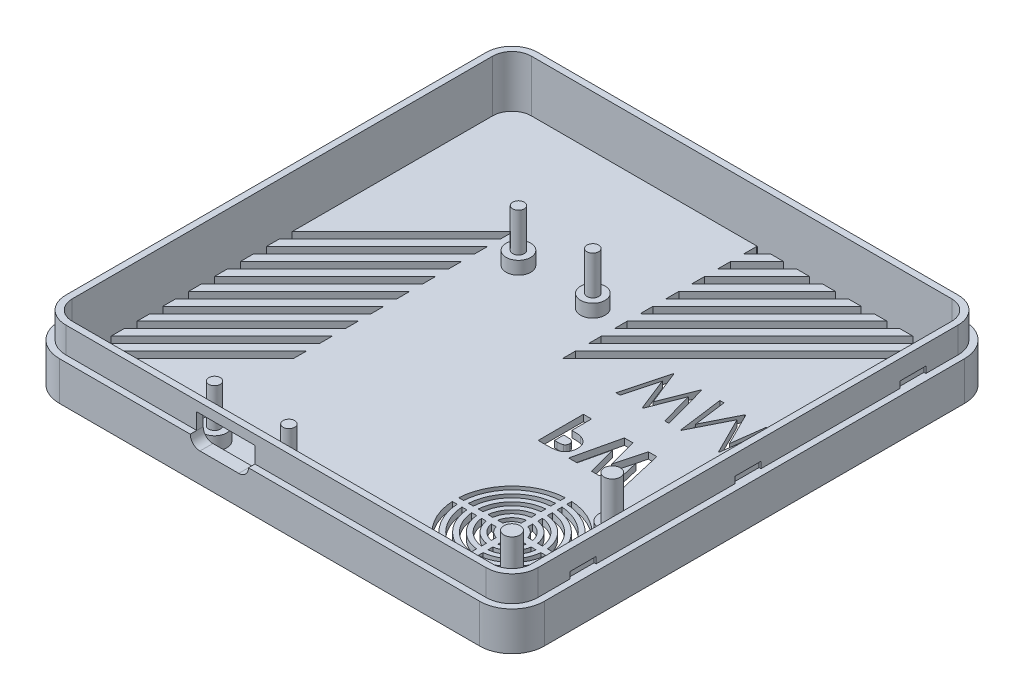
SolidWorks part; units mm, degrees
material "ABS"
ref_plane "Płaszczyzna przednia" through (0, 0, 0) normal (0, 0, 1) x (1, 0, 0)
ref_plane "Płaszczyzna górna" through (0, 0, 0) normal (0, 1, 0) x (1, 0, 0)
ref_plane "Płaszczyzna prawa" through (0, 0, 0) normal (1, 0, 0) x (0, 0, -1)
sketch "Szkic1" plane through (0, 0, 0) normal (0, 1, 0) x (1, 0, 0)
  line L0 (0, 0) -> (0, 75)
  line L1 (0, 75) -> (75, 75)
  line L2 (75, 75) -> (75, 0)
  line L3 (75, 0) -> (0, 0)
  dimension "D1" = 75
  dimension "D2" = 75
extrude "Dodanie-wyciągnięcie1" add sketch "Szkic1" along normal blind 10
fillet "Zaokrąglenie1" radius 5 4 edges at (0, 5, 0) (0, 5, -75) (75, 5, -75) (75, 5, 0)
sketch "Szkic4" plane through (0, 10, 0) normal (0, 1, 0) x (1, 0, 0)
  line L8 (2, 70) -> (2, 5)
  line L9 (5, 2) -> (70, 2)
  line L10 (73, 5) -> (73, 70)
  line L11 (70, 73) -> (5, 73)
  line L12 (2, 70) -> (2, 5)
  line L13 (5, 2) -> (70, 2)
  line L14 (73, 5) -> (73, 70)
  line L15 (70, 73) -> (5, 73)
  arc A8 (2, 5) -> (5, 2) centre (5, 5) ccw
  arc A9 (70, 2) -> (73, 5) centre (70, 5) ccw
  arc A10 (73, 70) -> (70, 73) centre (70, 70) ccw
  arc A11 (5, 73) -> (2, 70) centre (5, 70) ccw
  arc A12 (2, 5) -> (5, 2) centre (5, 5) ccw
  arc A13 (70, 2) -> (73, 5) centre (70, 5) ccw
  arc A14 (73, 70) -> (70, 73) centre (70, 70) ccw
  arc A15 (5, 73) -> (2, 70) centre (5, 70) ccw
  dimension "D1" = 2
extrude "Wytnij-wyciągnięcie1" cut sketch "Szkic4" against normal blind 8
sketch "Szkic6" plane through (0, 10, 0) normal (0, 1, 0) x (1, 0, 0)
  line L0 (70, 75) -> (5, 75)
  line L1 (0, 70) -> (0, 5)
  line L2 (5, 0) -> (70, 0)
  line L3 (75, 5) -> (75, 70)
  line L8 (1, 70) -> (1, 5)
  line L9 (5, 1) -> (70, 1)
  line L10 (74, 5) -> (74, 70)
  line L11 (70, 74) -> (5, 74)
  line L12 (1, 70) -> (1, 5)
  line L13 (5, 1) -> (70, 1)
  line L14 (74, 5) -> (74, 70)
  line L15 (70, 74) -> (5, 74)
  arc A0 (5, 75) -> (0, 70) centre (5, 70) ccw
  arc A1 (0, 5) -> (5, 0) centre (5, 5) ccw
  arc A2 (70, 0) -> (75, 5) centre (70, 5) ccw
  arc A3 (75, 70) -> (70, 75) centre (70, 70) ccw
  arc A8 (1, 5) -> (5, 1) centre (5, 5) ccw
  arc A9 (70, 1) -> (74, 5) centre (70, 5) ccw
  arc A10 (74, 70) -> (70, 74) centre (70, 70) ccw
  arc A11 (5, 74) -> (1, 70) centre (5, 70) ccw
  arc A12 (1, 5) -> (5, 1) centre (5, 5) ccw
  arc A13 (70, 1) -> (74, 5) centre (70, 5) ccw
  arc A14 (74, 70) -> (70, 74) centre (70, 70) ccw
  arc A15 (5, 74) -> (1, 70) centre (5, 70) ccw
  dimension "D1" = 1
  dimension "D3" = 1
extrude "Wytnij-wyciągnięcie2" cut sketch "Szkic6" against normal blind 4
sketch "Szkic7" plane through (0, 2, 0) normal (0, 1, 0) x (1, 0, 0)
  line L0 (2, 70) -> (2, 5) construction
  line L1 (5, 0) -> (70, 0) construction
  line L2 (0, 70) -> (0, 5) construction
  line L5 (29.75, 52) -> (29.75, 3.8449) construction
  circle A0 centre (24, 52) radius 0.9
  circle A1 centre (35.5, 52) radius 0.9005
  circle A2 centre (24, 5) radius 0.9
  circle A3 centre (35.5, 5) radius 0.9
  circle A4 centre (24, 52) radius 1.9
  circle A5 centre (35.5, 52) radius 1.9005
  circle A6 centre (35.5, 5) radius 1.9
  circle A7 centre (24, 5) radius 1.9
  point P24 (0, 0)
  dimension "D1" = 22
  dimension "D3" = 1.8
  dimension "D5" = 1.801
  dimension "D7" = 1.8
  dimension "D10" = 11.5
  dimension "D11" = 1.8
  dimension "D2" = 5
  dimension "D4" = 11.5
  dimension "D6" = 5
  dimension "D8" = 47
  dimension "D9" = 24
  dimension "D12" = 47
  dimension "D14" = 5.75
  dimension "D13" = 1
extrude "Dodanie-wyciągnięcie2" add sketch "Szkic7" along normal blind 2
sketch "Szkic9" plane through (0, 2, 0) normal (0, 1, 0) x (1, 0, 0)
  line L4 (2, 70) -> (2, 5)
  line L5 (5, 2) -> (70, 2)
  line L6 (73, 5) -> (73, 70)
  line L7 (70, 73) -> (5, 73)
  line L8 (2, 70) -> (2, 5)
  line L9 (5, 2) -> (70, 2)
  line L10 (73, 5) -> (73, 70)
  line L11 (70, 73) -> (5, 73)
  circle A0 centre (35.5, 52) radius 0.9005 construction
  circle A1 centre (35.5, 52) radius 0.9005
  circle A2 centre (35.5, 5) radius 0.9 construction
  circle A3 centre (24, 5) radius 0.9 construction
  arc A4 (5, 73) -> (2, 70) centre (5, 70) ccw
  arc A5 (2, 5) -> (5, 2) centre (5, 5) ccw
  arc A6 (70, 2) -> (73, 5) centre (70, 5) ccw
  arc A7 (73, 70) -> (70, 73) centre (70, 70) ccw
  arc A8 (5, 73) -> (2, 70) centre (5, 70) ccw
  arc A9 (2, 5) -> (5, 2) centre (5, 5) ccw
  arc A10 (70, 2) -> (73, 5) centre (70, 5) ccw
  arc A11 (73, 70) -> (70, 73) centre (70, 70) ccw
  circle A12 centre (24, 52) radius 0.9 construction
  circle A13 centre (35.5, 5) radius 0.9
  circle A14 centre (24, 5) radius 0.9
  circle A15 centre (24, 52) radius 0.9
  dimension "D1" = 0
extrude "Dodanie-wyciągnięcie3" add sketch "Szkic9" along normal blind 8 contours A15 | A1 | A14 | A13
sketch "Szkic10" plane through (0, 2, 0) normal (0, 1, 0) x (1, 0, 0)
  line L0 (73, 5) -> (73, 70) construction
  line L1 (5, 2) -> (70, 2) construction
  circle A0 centre (67, 23.5) radius 1.25
  circle A1 centre (67, 8) radius 1.25
  dimension "D1" = 2.5
  dimension "D2" = 2.5
  dimension "D4" = 6
  dimension "D3" = 15.5
  dimension "D5" = 6
  dimension "D6" = 21.5
extrude "Dodanie-wyciągnięcie4" add sketch "Szkic10" along normal blind 8
sketch "Szkic11" plane through (0, 2, 0) normal (0, 1, 0) x (1, 0, 0)
  line L4 (2, 70) -> (2, 5)
  line L5 (5, 2) -> (70, 2)
  line L6 (73, 5) -> (73, 70)
  line L7 (70, 73) -> (5, 73)
  line L8 (2, 70) -> (2, 5)
  line L9 (5, 2) -> (70, 2)
  line L10 (73, 5) -> (73, 70)
  line L11 (70, 73) -> (5, 73)
  circle A0 centre (67, 8) radius 1.25 construction
  circle A1 centre (67, 23.5) radius 1.25 construction
  circle A2 centre (67, 8) radius 1.25
  circle A3 centre (67, 23.5) radius 1.25
  arc A4 (5, 73) -> (2, 70) centre (5, 70) ccw
  arc A5 (2, 5) -> (5, 2) centre (5, 5) ccw
  arc A6 (70, 2) -> (73, 5) centre (70, 5) ccw
  arc A7 (73, 70) -> (70, 73) centre (70, 70) ccw
  arc A8 (5, 73) -> (2, 70) centre (5, 70) ccw
  arc A9 (2, 5) -> (5, 2) centre (5, 5) ccw
  arc A10 (70, 2) -> (73, 5) centre (70, 5) ccw
  arc A11 (73, 70) -> (70, 73) centre (70, 70) ccw
  circle A12 centre (67, 23.5) radius 2
  circle A13 centre (67, 8) radius 2
  circle M9 centre (67, 8) radius 1.25
  circle M10 centre (67, 23.5) radius 1.25
  dimension "D1" = 0
  dimension "D2" = 0.75
extrude "Dodanie-wyciągnięcie5" add sketch "Szkic11" along normal blind 1.5 contours A12 M10 | A13 M9
sketch "Szkic14" plane through (0, 2, 0) normal (0, 1, 0) x (1, 0, 0)
  line L0 (52, 73) -> (2, 23)
  line L1 (70, 73) -> (5, 73) construction
  line L2 (2, 70) -> (2, 5) construction
  line L3 (54, 73) -> (2, 21)
  line L4 (56, 73) -> (2, 19)
  line L5 (58, 73) -> (2, 17)
  line L6 (60, 73) -> (2, 15)
  line L7 (2, 23) -> (2, 21)
  line L8 (62, 73) -> (2, 13)
  line L9 (2, 25) -> (50, 73)
  line L10 (46, 73) -> (2, 29)
  line L12 (2, 27) -> (48, 73)
  line L13 (2, 11) -> (64, 73)
  line L14 (2, 9) -> (66, 73)
  line L15 (2, 7) -> (68, 73)
  line L16 (2, 5) -> (70, 73)
  line L18 (2, 19) -> (2, 17)
  line L19 (2, 15) -> (2, 13)
  line L20 (2, 11) -> (2, 9)
  line L21 (2, 7) -> (2, 5)
  line L22 (48, 73) -> (50, 73)
  line L23 (52, 73) -> (54, 73)
  line L24 (56, 73) -> (58, 73)
  line L25 (60, 73) -> (62, 73)
  line L26 (64, 73) -> (66, 73)
  line L27 (68, 73) -> (70, 73)
  line L30 (2, 70) -> (2, 5) construction
  line L31 (2, 27) -> (2, 25)
  line L32 (2, 31) -> (44, 73)
  line L33 (44, 73) -> (46, 73)
  line L34 (2, 31) -> (2, 29)
  line L35 (2, 33) -> (42, 73)
  line L36 (38, 73) -> (2, 37)
  line L37 (40, 73) -> (2, 35)
  line L38 (2, 39) -> (36, 73)
  line L40 (19.1028, 55) -> (40, 55)
  line L41 (39.899, 13) -> (19.1028, 13)
  line L42 (39.899, 73) -> (39.899, 13)
  line L45 (19.1028, 13) -> (19.1028, 22.1028)
  line L46 (19.1028, 73) -> (39.899, 73)
  line L49 (19.1028, 73) -> (19.1028, 13)
  circle A2 centre (35.5, 52) radius 0.9005 construction
  line M13 (2, 70) -> (2, 5)
  line M19 (70, 73) -> (5, 73)
  dimension "D23" = 3
  dimension "D1" = 2
  dimension "D2" = 2
  dimension "D3" = 2
  dimension "D4" = 2
  dimension "D5" = 2
  dimension "D6" = 2
  dimension "D7" = 2
  dimension "D8" = 2
  dimension "D9" = 2
  dimension "D10" = 2
  dimension "D11" = 2
  dimension "D12" = 2
  dimension "D13" = 2
  dimension "D14" = 2
  dimension "D15" = 2
  dimension "D16" = 2
  dimension "D17" = 2
  dimension "D18" = 2
  dimension "D19" = 60
  dimension "D20" = 20.7962
  dimension "D21" = 17.1028
  dimension "D22" = 0
sketch "Szkic15" plane through (0, 2, 0) normal (0, 1, 0) x (1, 0, 0)
  line L0 (59.75, 16.25) -> (69.75, 16.25)
  line L1 (58.75, 26.25) -> (59.75, 26.25)
  line L2 (58.75, 26.25) -> (58.75, 16.25)
  line L3 (58.75, 5.25) -> (59.75, 5.25)
  line L4 (59.75, 26.25) -> (59.75, 16.25)
  line L5 (48.75, 16.25) -> (58.75, 16.25)
  line L6 (48.75, 16.25) -> (48.75, 15.25)
  line L7 (48.75, 15.25) -> (58.75, 15.25)
  line L8 (69.75, 16.25) -> (69.75, 15.25)
  line L9 (59.75, 15.25) -> (69.75, 15.25)
  line L10 (59.75, 15.25) -> (59.75, 5.25)
  line L11 (58.75, 15.25) -> (58.75, 5.25)
  line L12 (59.75, 16.25) -> (59.25, 15.75)
  line L13 (58.75, 16.25) -> (59.75, 15.25) construction
  line L14 (59.75, 16.25) -> (58.75, 15.25) construction
  line L15 (73, 5) -> (73, 70) construction
  line L16 (5, 2) -> (70, 2) construction
  circle A0 centre (67, 23.5) radius 2 construction
  circle A1 centre (67, 23.5) radius 1.25 construction
  arc A2 (58.75, 16.8956) -> (58.1044, 16.25) centre (59.25, 15.75) ccw
  arc A3 (58.75, 17.6865) -> (57.3135, 16.25) centre (59.25, 15.75) ccw
  arc A4 (58.75, 18.4542) -> (56.5458, 16.25) centre (59.25, 15.75) ccw
  arc A5 (58.75, 19.2141) -> (55.7859, 16.25) centre (59.25, 15.75) ccw
  arc A6 (58.75, 19.9705) -> (55.0295, 16.25) centre (59.25, 15.75) ccw
  arc A7 (58.75, 20.7249) -> (54.2751, 16.25) centre (59.25, 15.75) ccw
  arc A8 (58.75, 21.4782) -> (53.5218, 16.25) centre (59.25, 15.75) ccw
  arc A9 (58.75, 22.2307) -> (52.7693, 16.25) centre (59.25, 15.75) ccw
  arc A10 (58.75, 22.9827) -> (52.0173, 16.25) centre (59.25, 15.75) ccw
  arc A11 (58.75, 23.7344) -> (51.2656, 16.25) centre (59.25, 15.75) ccw
  arc A12 (58.75, 24.4857) -> (50.5143, 16.25) centre (59.25, 15.75) ccw
  arc A13 (60.3956, 16.25) -> (59.75, 16.8956) centre (59.25, 15.75) ccw
  arc A14 (61.1865, 16.25) -> (59.75, 17.6865) centre (59.25, 15.75) ccw
  arc A15 (61.9542, 16.25) -> (59.75, 18.4542) centre (59.25, 15.75) ccw
  arc A16 (62.7141, 16.25) -> (59.75, 19.2141) centre (59.25, 15.75) ccw
  arc A17 (63.4705, 16.25) -> (59.75, 19.9705) centre (59.25, 15.75) ccw
  arc A18 (64.2249, 16.25) -> (59.75, 20.7249) centre (59.25, 15.75) ccw
  arc A19 (64.9782, 16.25) -> (59.75, 21.4782) centre (59.25, 15.75) ccw
  arc A20 (65.7307, 16.25) -> (59.75, 22.2307) centre (59.25, 15.75) ccw
  arc A21 (66.4827, 16.25) -> (59.75, 22.9827) centre (59.25, 15.75) ccw
  arc A22 (67.2344, 16.25) -> (59.75, 23.7344) centre (59.25, 15.75) ccw
  arc A23 (67.9857, 16.25) -> (59.75, 24.4857) centre (59.25, 15.75) ccw
  arc A24 (59.75, 7.0143) -> (67.9857, 15.25) centre (59.25, 15.75) ccw
  arc A25 (59.75, 7.7656) -> (67.2344, 15.25) centre (59.25, 15.75) ccw
  arc A26 (59.75, 8.5173) -> (66.4827, 15.25) centre (59.25, 15.75) ccw
  arc A27 (59.75, 9.2693) -> (65.7307, 15.25) centre (59.25, 15.75) ccw
  arc A28 (59.75, 10.0218) -> (64.9782, 15.25) centre (59.25, 15.75) ccw
  arc A29 (59.75, 10.7751) -> (64.2249, 15.25) centre (59.25, 15.75) ccw
  arc A30 (59.75, 11.5295) -> (63.4705, 15.25) centre (59.25, 15.75) ccw
  arc A31 (59.75, 12.2859) -> (62.7141, 15.25) centre (59.25, 15.75) ccw
  arc A32 (59.75, 13.0458) -> (61.9542, 15.25) centre (59.25, 15.75) ccw
  arc A33 (59.75, 13.8135) -> (61.1865, 15.25) centre (59.25, 15.75) ccw
  arc A34 (59.75, 14.6044) -> (60.3956, 15.25) centre (59.25, 15.75) ccw
  arc A35 (58.1044, 15.25) -> (58.75, 14.6044) centre (59.25, 15.75) ccw
  arc A36 (57.3135, 15.25) -> (58.75, 13.8135) centre (59.25, 15.75) ccw
  arc A37 (56.5458, 15.25) -> (58.75, 13.0458) centre (59.25, 15.75) ccw
  arc A38 (55.7859, 15.25) -> (58.75, 12.2859) centre (59.25, 15.75) ccw
  arc A39 (55.0295, 15.25) -> (58.75, 11.5295) centre (59.25, 15.75) ccw
  arc A40 (54.2751, 15.25) -> (58.75, 10.7751) centre (59.25, 15.75) ccw
  arc A41 (53.5218, 15.25) -> (58.75, 10.0218) centre (59.25, 15.75) ccw
  arc A42 (52.7693, 15.25) -> (58.75, 9.2693) centre (59.25, 15.75) ccw
  arc A43 (52.0173, 15.25) -> (58.75, 8.5173) centre (59.25, 15.75) ccw
  arc A44 (51.2656, 15.25) -> (58.75, 7.7656) centre (59.25, 15.75) ccw
  arc A45 (50.5143, 15.25) -> (58.75, 7.0143) centre (59.25, 15.75) ccw
  dimension "D4" = 10
  dimension "D9" = 2.5
  dimension "D10" = 4
  dimension "D11" = 5.5
  dimension "D12" = 7
  dimension "D13" = 8.5
  dimension "D14" = 10
  dimension "D15" = 11.5
  dimension "D16" = 13
  dimension "D17" = 14.5
  dimension "D18" = 16
  dimension "D19" = 17.5
  dimension "D1" = 1
  dimension "D2" = 1
  dimension "D3" = 7.25
  dimension "D5" = 10
  dimension "D6" = 10
  dimension "D7" = 10
  dimension "D8" = 7.25
  dimension "D20" = 13.75
  dimension "D21" = 13.75
extrude "Wytnij-wyciągnięcie5" cut sketch "Szkic15" against normal through all both and the other way through all contours L2 A2 L5 | L0 A13 L4 | L10 A34 L9 | L7 A35 L11 | L2 A4 L5 A3 | L7 A37 L11 A36 | A33 L10 A32 L9 | L0 A15 L4 A14 | L0 A17 L4 A16 | L0 A19 L4 A18 | L0 A21 L4 A20 | L0 A23 L4 A22 | L2 A12 L5 A11 | L2 A10 L5 A9 | L2 A8 L5 A7 | L2 A6 L5 A5 | L7 A39 L11 A38 | L7 A41 L11 A40 | L7 A43 L11 A42 | A29 L10 A28 L9 | A27 L10 A26 L9 | A25 L10 A24 L9 | L7 A45 L11 A44 | A31 L10 A30 L9
sketch "Szkic16" plane through (0, 0, 0) normal (0, -1, 0) x (1, 0, 0)
  line L8 (70, -1) -> (5, -1)
  line L9 (1, -5) -> (1, -70)
  line L10 (5, -74) -> (70, -74)
  line L11 (74, -70) -> (74, -5)
  line L12 (70, -1) -> (5, -1)
  line L13 (1, -5) -> (1, -70)
  line L14 (5, -74) -> (70, -74)
  line L15 (74, -70) -> (74, -5)
  arc A8 (5, -1) -> (1, -5) centre (5, -5) ccw
  arc A9 (1, -70) -> (5, -74) centre (5, -70) ccw
  arc A10 (70, -74) -> (74, -70) centre (70, -70) ccw
  arc A11 (74, -5) -> (70, -1) centre (70, -5) ccw
  arc A12 (5, -1) -> (1, -5) centre (5, -5) ccw
  arc A13 (1, -70) -> (5, -74) centre (5, -70) ccw
  arc A14 (70, -74) -> (74, -70) centre (70, -70) ccw
  arc A15 (74, -5) -> (70, -1) centre (70, -5) ccw
  dimension "D1" = 1
extrude "Wytnij-wyciągnięcie6" cut sketch "Szkic16" against normal blind 1
sketch "Szkic18" plane through (0, 1, 0) normal (0, -1, 0) x (1, 0, 0)
  text T1 "<b>PW</b>\r\nWMT" font "Century Gothic" height 7
  point P0 (48.1743, -37.0643)
extrude "Wytnij-wyciągnięcie9" cut sketch "Szkic18" against normal through all both and the other way through all
sketch "Szkic19" plane through (0, 0, -2) normal (0, 0, -1) x (-1, 0, 0)
  line L0 (-29.75, 2) -> (-29.75, 10) construction
  line L1 (-5, 2) -> (-70, 2) construction
  line L3 (-5, 6) -> (-5, 10) construction
  line L7 (0, 0) -> (0, 6) construction
  line L8 (-32.75, 4.5) -> (-26.75, 4.5)
  line L9 (-34.25, 6) -> (-34.25, 8.5)
  line L10 (-34.25, 8.5) -> (-25.25, 8.5)
  line L11 (-25.25, 6) -> (-25.25, 8.5)
  arc A1 (-25.25, 6) -> (-26.75, 4.5) centre (-26.75, 6) cw
  arc A2 (-32.75, 4.5) -> (-34.25, 6) centre (-32.75, 6) cw
  point P16 (-34.25, 4.5)
  dimension "D2" = 1.5
  dimension "D1" = 29.75
  dimension "D4" = 9
  dimension "D5" = 4
  dimension "D6" = 4.5
  dimension "D7" = 2.5
sketch "Szkic20" plane through (1, 0, 0) normal (-1, 0, 0) x (0, 0, 1)
  line L0 (-70, 6) -> (-5, 6) construction
  line L1 (-65, 6) -> (-61, 6)
  line L2 (-65, 6) -> (-65, 7)
  line L3 (-65, 7) -> (-61, 7)
  line L4 (-61, 6) -> (-61, 7)
  line L5 (-14, 7) -> (-10, 7)
  line L6 (-14, 6) -> (-14, 7)
  line L7 (-14, 6) -> (-10, 6)
  line L8 (-10, 6) -> (-10, 7)
  line L9 (0, 6) -> (0, 0) construction
  line L10 (-39.5, 7) -> (-35.5, 7)
  line L11 (-35.5, 6) -> (-35.5, 7)
  line L12 (-39.5, 6) -> (-35.5, 6)
  line L13 (-39.5, 6) -> (-39.5, 7)
  point P14 (-63, 6)
  point P18 (-37.5, 6)
  dimension "D1" = 1
  dimension "D2" = 4
  dimension "D3" = 10
  dimension "D5" = 10
  dimension "D7" = 25.5
  dimension "D4" = 2
  dimension "D6" = 2
extrude "Wytnij-wyciągnięcie11" cut sketch "Szkic20" against normal blind 0.3
sketch "Szkic21" plane through (74, 0, 0) normal (1, 0, 0) x (0, 0, -1)
  line L0 (5, 6) -> (70, 6) construction
  line L1 (10, 6) -> (14, 6)
  line L2 (10, 6) -> (10, 7)
  line L3 (10, 7) -> (14, 7)
  line L4 (14, 6) -> (14, 7)
  line L5 (0, 0) -> (0, 6) construction
  line L6 (61, 7) -> (65, 7)
  line L7 (61, 6) -> (61, 7)
  line L8 (61, 6) -> (65, 6)
  line L9 (65, 6) -> (65, 7)
  line L10 (75, 6) -> (75, 0) construction
  line L11 (35.5, 7) -> (39.5, 7)
  line L12 (35.5, 6) -> (35.5, 7)
  line L13 (35.5, 6) -> (39.5, 6)
  line L14 (39.5, 6) -> (39.5, 7)
  point P15 (12, 6)
  point P19 (37.5, 6)
  dimension "D1" = 4
  dimension "D2" = 1
  dimension "D3" = 10
  dimension "D5" = 10
  dimension "D7" = 25.5
  dimension "D4" = 2
  dimension "D6" = 2
extrude "Wytnij-wyciągnięcie12" cut sketch "Szkic21" against normal blind 0.3
ref_plane "Płaszczyzna1" through (0, 0, -25) normal (0, 0, -1) x (-1, 0, 0)
extrude "Wytnij-wyciągnięcie13" cut sketch "Szkic19" along direction (0, 0, 1) on the side against the normal blind 40
extrude "Wytnij-wyciągnięcie16" cut sketch "Szkic14" against normal blind 2 contours L49 L38 L36 M13 | L49 L37 L35 M13 | L49 L32 L10 M13 | L49 L12 L9 M13 | L49 L0 L3 M13 | L49 L4 L5 M13 | L49 L6 L8 M13 | L49 L13 L14 M13 | L49 L15 L16 M13 | L37 L42 L35 M19 | L32 L42 L10 M19 | L12 L42 L9 M19 | L0 L42 L3 M19 | L4 L42 L40 L5 M19 | L6 L42 L8 M19 | L13 L42 L14 M19 | L15 L42 L16 M19
